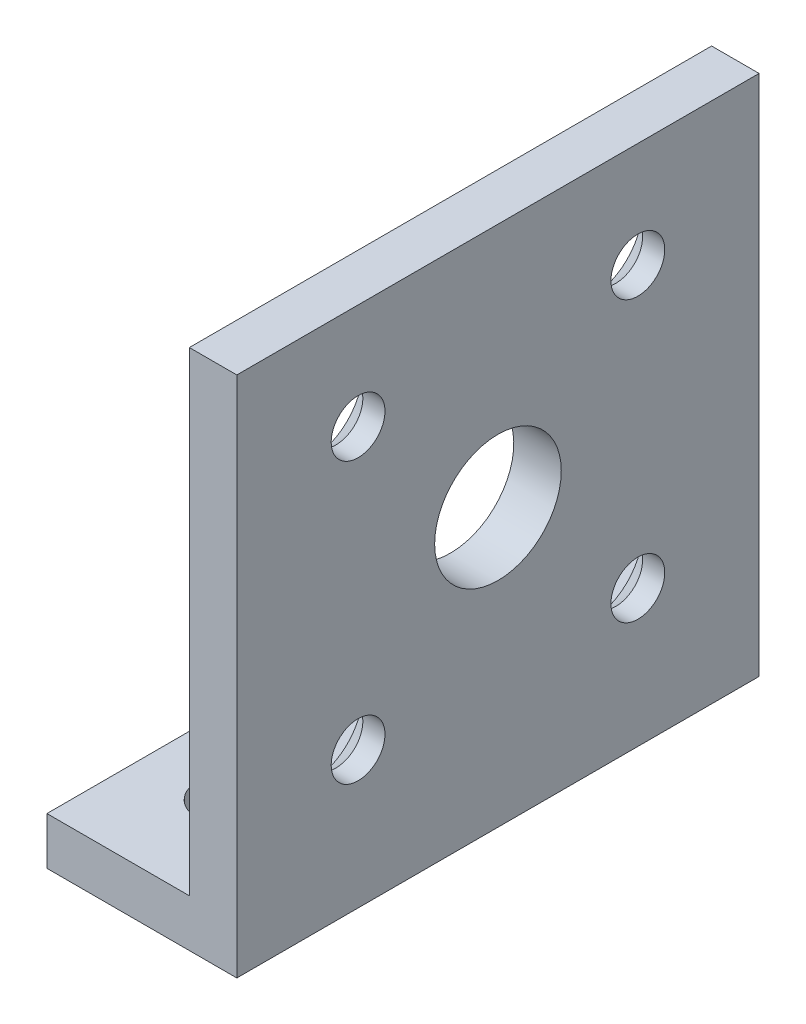
SolidWorks part; units mm, degrees
material "1060 合金"
ref_plane "前视基准面" through (0, 0, 0) normal (0, 0, 1) x (1, 0, 0)
ref_plane "上视基准面" through (0, 0, 0) normal (0, 1, 0) x (1, 0, 0)
ref_plane "右视基准面" through (0, 0, 0) normal (1, 0, 0) x (0, 0, -1)
sketch "草图1" plane through (0, 0, 0) normal (0, 0, 1) x (1, 0, 0)
  line L0 (0, 33) -> (0, 0)
  line L1 (0, 0) -> (-12, 0)
  dimension "D1" = 12
  dimension "D2" = 33
extrude "拉伸-薄壁1" add sketch "草图1" along normal mid plane 33 thin
sketch "草图4" plane through (-3, 0, 0) normal (-1, 0, 0) x (0, 0, 1)
  line L14 (16.5, 0) -> (-16.5, 0) construction
  line L15 (16.5, 0) -> (-16.5, 0) construction
  circle A0 centre (0, 17.5) radius 16.5 construction
  circle A1 centre (0, 17.5) radius 4
  dimension "D1" = 33
  dimension "D2" = 8
  dimension "D3" = 1
extrude "切除-拉伸1" cut sketch "草图4" against normal up to next
hole_wizard "打孔尺寸(%根据十字)槽半沉头木螺钉的类型2" positions "草图3" profile "草图2" countersink size "M3" standard "GB"
sketch "草图3" plane through (-3, 0, 0) normal (-1, 0, 0) x (0, 0, 1)
  line L1 (0, 17.5) -> (8.8388, 8.6612) construction
  line L3 (0, 17.5) -> (5.8968, 17.5) construction
  circle A0 centre (0, 17.5) radius 12.5
  circle A1 centre (0, 17.5) radius 4 construction
  point P6 (8.8388, 8.6612)
  point P38 (-8.8388, 8.6612)
  point P39 (-8.8388, 26.3388)
  point P40 (8.8388, 26.3388)
  dimension "D1" = 25
  dimension "D3" = 45
  dimension "D4" = 4
sketch "草图2" plane through (-3, 8.6612, 8.8388) normal (0, 1, 0) x (0, 0, 1)
  line L0 (0, 0) -> (0, 11.0215)
  line L1 (0, 11.0215) -> (1.7, 10)
  line L2 (1.7, 10) -> (1.7, 1.6)
  line L3 (1.7, 1.6) -> (3.3, 0)
  line L5 (3.3, 0) -> (0, 0)
  line L6 (-1.7, 1.6) -> (-3.3, 0) construction
  line L10 (0, 11.0215) -> (-1.7, 10) construction
  line L11 (0, -6.35) -> (0, 107.95) construction
  dimension "孔直径" = 3.4
  dimension "孔深度" = 10
  dimension "近端锥形沉头孔直径" = 6.6
  dimension "近端锥形沉头孔角度" = 90
  dimension "导头角度" = 118
hole_wizard "M4 螺纹孔1" positions "草图7" profile "草图6" tap size "M4" standard "GB" end condition up to next
sketch "草图7" plane through (0, 3, 0) normal (0, 1, 0) x (1, 0, 0)
  line L0 (0, 0) -> (-18.9251, 0) construction
  line L3 (-12, -16.5) -> (-12, 16.5) construction
  point P0 (-7, 10)
  point P12 (-7, -10)
  dimension "D1" = 20
  dimension "D2" = 5
sketch "草图6" plane through (-7, 3, -10) normal (1, 0, 0) x (0, 0, 1)
  line L0 (0, 0) -> (0, 3)
  line L1 (0, 3) -> (2, 3)
  line L2 (2, 3) -> (2, 0)
  line L5 (2, 0) -> (0, 0)
  line L11 (0, -6.35) -> (0, 107.95) construction
  dimension "螺纹线主直径" = 4
  dimension "通孔螺纹孔钻头深度" = 3
move or copy body "实体-移动/复制1" [suppressed] bodies to move or copy 109
